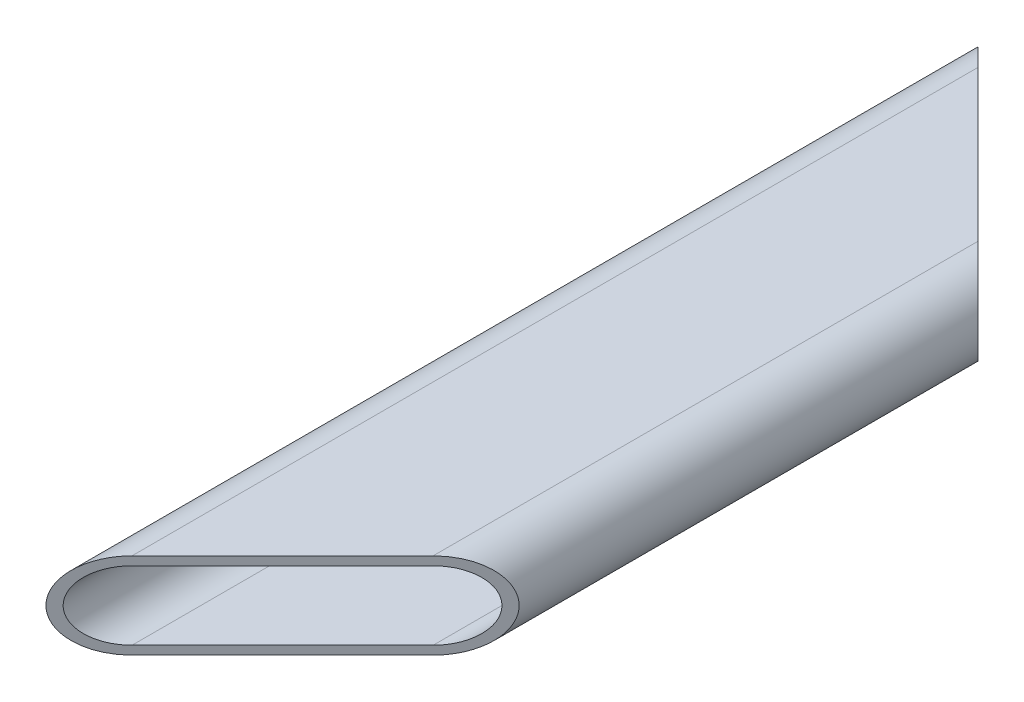
SolidWorks part; units mm, degrees
ref_plane "Front Plane" through (0, 0, 0) normal (0, 0, 1) x (1, 0, 0)
ref_plane "Top Plane" through (0, 0, 0) normal (0, 1, 0) x (1, 0, 0)
ref_plane "Right Plane" through (0, 0, 0) normal (1, 0, 0) x (0, 0, -1)
sketch "Sketch1" plane through (0, 0, 0) normal (0, 0, 1) x (1, 0, 0)
  line L0 (0, 0) -> (21, 0) construction
  line L1 (0, 6) -> (21, 6)
  line L2 (0, -6) -> (21, -6)
  line L3 (0, 4.8) -> (21, 4.8)
  line L4 (0, -4.8) -> (21, -4.8)
  arc A0 (0, 6) -> (0, -6) centre (0, 0) ccw
  arc A1 (21, -6) -> (21, 6) centre (21, 0) ccw
  arc A2 (21, -4.8) -> (21, 4.8) centre (21, 0) ccw
  arc A3 (0, 4.8) -> (0, -4.8) centre (0, 0) ccw
  point P3 (10.5, 0)
  dimension "D1" = 12
  dimension "D2" = 21
  dimension "D3" = 1.2
extrude "Boss-Extrude1" add sketch "Sketch1" along normal blind 130
sketch "Sketch2" plane through (0, 6, 0) normal (0, 1, 0) x (1, 0, 0)
  line L0 (-6, 0) -> (27, -33)
  line L1 (27, -130) -> (27, 0) construction
  line L2 (27, -33) -> (27, 0)
  line L3 (27, 0) -> (-6, 0)
  line L4 (-6, -130) -> (27, -97)
  line L5 (27, -97) -> (27, -130)
  line L6 (27, -130) -> (-6, -130)
  dimension "D1" = 45
  dimension "D2" = 45
extrude "Cut-Extrude1" cut sketch "Sketch2" against normal blind 30
